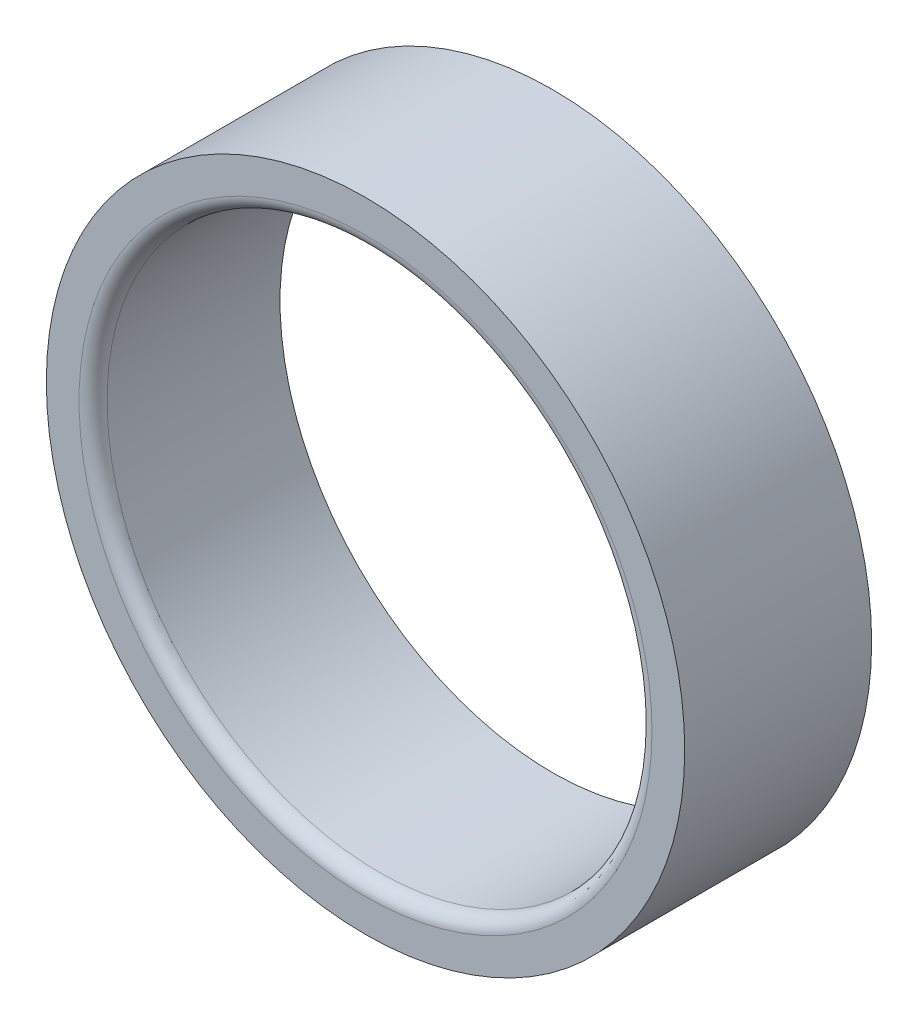
SolidWorks part; units mm, degrees
ref_plane "Front Plane" through (0, 0, 0) normal (0, 0, 1) x (1, 0, 0)
ref_plane "Top Plane" through (0, 0, 0) normal (0, 1, 0) x (1, 0, 0)
ref_plane "Right Plane" through (0, 0, 0) normal (1, 0, 0) x (0, 0, -1)
sketch "Sketch1" plane through (0, 0, 0) normal (0, 0, 1) x (1, 0, 0)
  circle A0 centre (0, 0) radius 29.15
  circle A1 centre (0, 0) radius 34.15
  dimension "D1" = 58.3
  dimension "D2" = 5
extrude "Boss-Extrude1" add sketch "Sketch1" along normal blind 20
fillet "Fillet1" radius 1.5 1 edges at (29.15, 0, 20)
